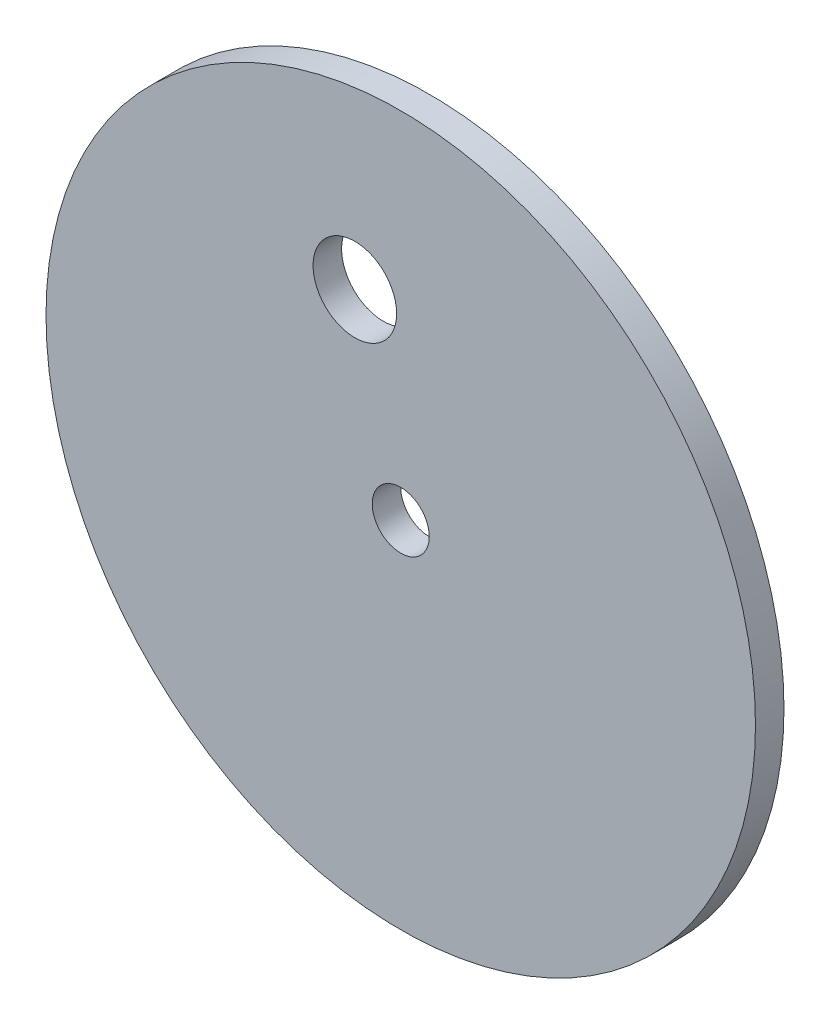
SolidWorks part; units mm, degrees
ref_plane "正面" through (0, 0, 0) normal (0, 0, 1) x (1, 0, 0)
ref_plane "平面" through (0, 0, 0) normal (0, 1, 0) x (1, 0, 0)
ref_plane "右側面" through (0, 0, 0) normal (1, 0, 0) x (0, 0, -1)
sketch "ｽｹｯﾁ1" plane through (0, 0, 0) normal (0, 0, 1) x (1, 0, 0)
  circle A0 centre (0, 0) radius 124.4
  circle A1 centre (-16.0934, 62.0164) radius 14.6495
  circle A2 centre (0, 0) radius 10
extrude "ﾎﾞｽ - 押し出し1" add sketch "ｽｹｯﾁ1" along normal blind 10
